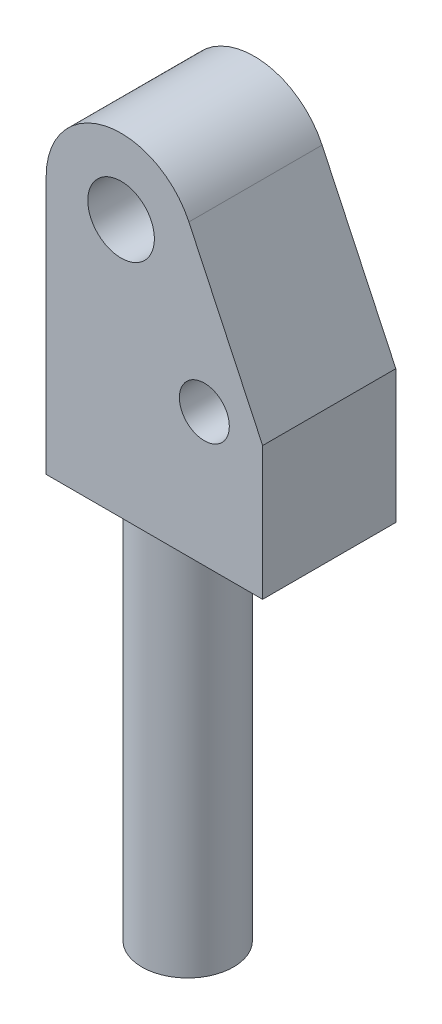
SolidWorks part; units mm, degrees
ref_plane "Front Plane" through (0, 0, 0) normal (0, 0, 1) x (1, 0, 0)
ref_plane "Top Plane" through (0, 0, 0) normal (0, 1, 0) x (1, 0, 0)
ref_plane "Right Plane" through (0, 0, 0) normal (1, 0, 0) x (0, 0, -1)
sketch "Sketch1" plane through (0, 0, 0) normal (0, 1, 0) x (1, 0, 0)
  circle A0 centre (0, 0) radius 5.5
  dimension "D1" = 11
extrude "Boss-Extrude1" add sketch "Sketch1" along normal blind 48
sketch "Sketch3" plane through (0, 0, 0) normal (0, 0, 1) x (1, 0, 0)
  line L0 (0, 0) -> (0, 48) construction
  line L1 (5.5, 48) -> (-5.5, 48) construction
  line L2 (0, 48) -> (17, 48)
  line L3 (17, 48) -> (17, 64)
  line L4 (17, 64) -> (8.1443, 82.8302)
  line L5 (0, 48) -> (-9, 48)
  line L6 (-9, 48) -> (-9, 79)
  arc A0 (8.1443, 82.8302) -> (-9, 79) centre (0, 79) ccw
  circle A1 centre (0, 79) radius 4
  circle A2 centre (10, 64) radius 3
  point P14 (0, 0)
  point P15 (0, 0)
  point P16 (0, 0)
  dimension "D1" = 8
  dimension "D2" = 9
  dimension "D3" = 6
  dimension "D4" = 7
  dimension "D5" = 16
  dimension "D6" = 15
  dimension "D7" = 26
extrude "Boss-Extrude2" add sketch "Sketch3" along normal mid plane 16
chamfer "Chamfer1" distance 1 angle 45 1 edges at (0, 48, 5.5)
